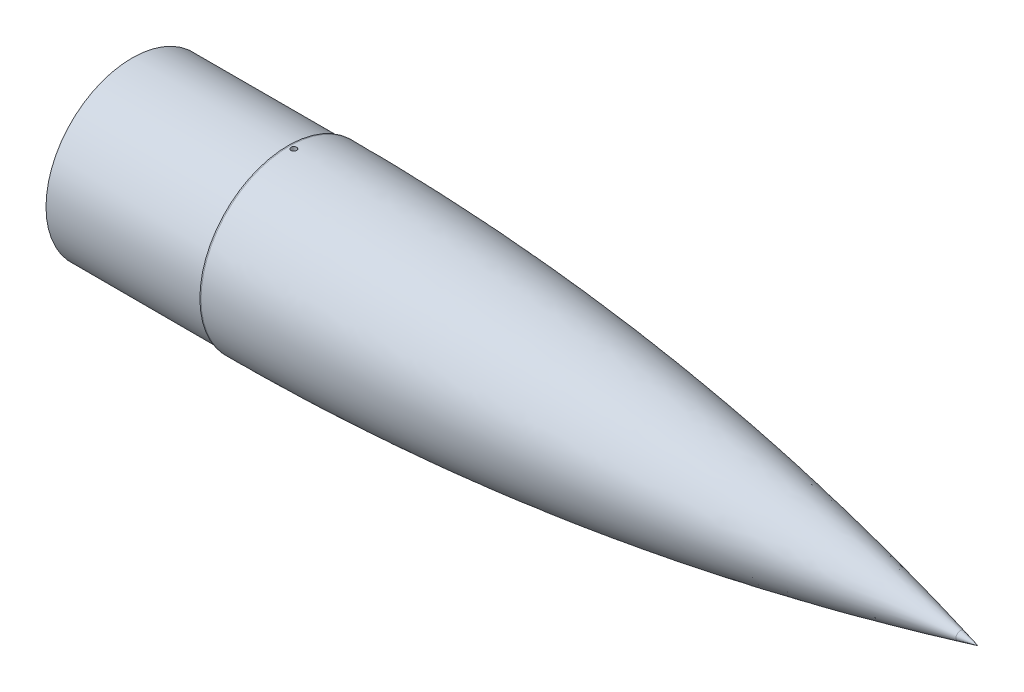
SolidWorks part; units mm, degrees
material "ABS"
ref_plane "Plan de face" through (0, 0, 0) normal (0, 0, 1) x (1, 0, 0)
ref_plane "Plan de dessus" through (0, 0, 0) normal (0, 1, 0) x (1, 0, 0)
ref_plane "Plan de droite" through (0, 0, 0) normal (1, 0, 0) x (0, 0, -1)
sketch "Esquisse1" plane through (0, 0, 0) normal (0, 0, 1) x (1, 0, 0)
  line L0 (-218.2881, 0) -> (241.2348, 0) construction
  line L1 (-501.301, 74) -> (-500.301, 74)
  line L2 (-500.301, 74) -> (-205.033, 74) construction
  line L3 (-205.033, 74) -> (91.7647, 0) construction
  line L4 (-501.301, 78) -> (-500.301, 78)
  line L5 (-501.301, 74) -> (-501.301, 78)
  line L6 (92.7324, 3.8812) -> (108.299, 0)
  line L7 (108.299, 0) -> (91.7647, 0)
  spline S0 degree 1 poles (-500.301, 78) (92.7324, 3.8812) knots 0 0 1 1 construction
  spline S1 degree 2 poles (-500.301, 74) (-205.033, 74) (91.7647, 0) knots 0 0 0 1 1 1
  spline S2 degree 3 poles (-500.301, 78) (-475.6426, 78) (-426.3478, 77.2279) (-327.6554, 72.595) (-228.8804, 63.3296) (-130.009, 49.4319) (-68.1766, 38.8159) (-18.6875, 29.1651) (18.4399, 21.3483) (49.3915, 14.3513) (74.1524, 8.4657) (86.5458, 5.4237) (92.7324, 3.8812) knots 0 0 0 0 0.125 0.25 0.5 0.625 0.75 0.8125 0.875 0.9375 0.96875 1 1 1 1
  dimension "D1" = 78
  dimension "D2" = 14
  dimension "D3" = 1
  dimension "D5" = 4
  dimension "D7" = 609.6
revolve "Révolution3" add sketch "Esquisse1" angle 360 about L0
sketch "Esquisse2" plane through (-501.301, 0, 0) normal (-1, 0, 0) x (0, 0, 1)
  circle A0 centre (0, 0) radius 74
  circle A1 centre (0, 0) radius 76
  dimension "D1" = 152
  dimension "D2" = 148
extrude "Boss.-Extru.1" add sketch "Esquisse2" along normal blind 138
sketch "Esquisse3" plane through (0, 0, 0) normal (0, 1, 0) x (1, 0, 0)
  line L1 (-501.301, 78) -> (-501.301, -78) construction
  circle A0 centre (-496.301, 0) radius 2.5
  dimension "D1" = 5
  dimension "D2" = 5
extrude "Enlèv. mat.-Extru.1" cut sketch "Esquisse3" against normal through all both and the other way through all contours A0
